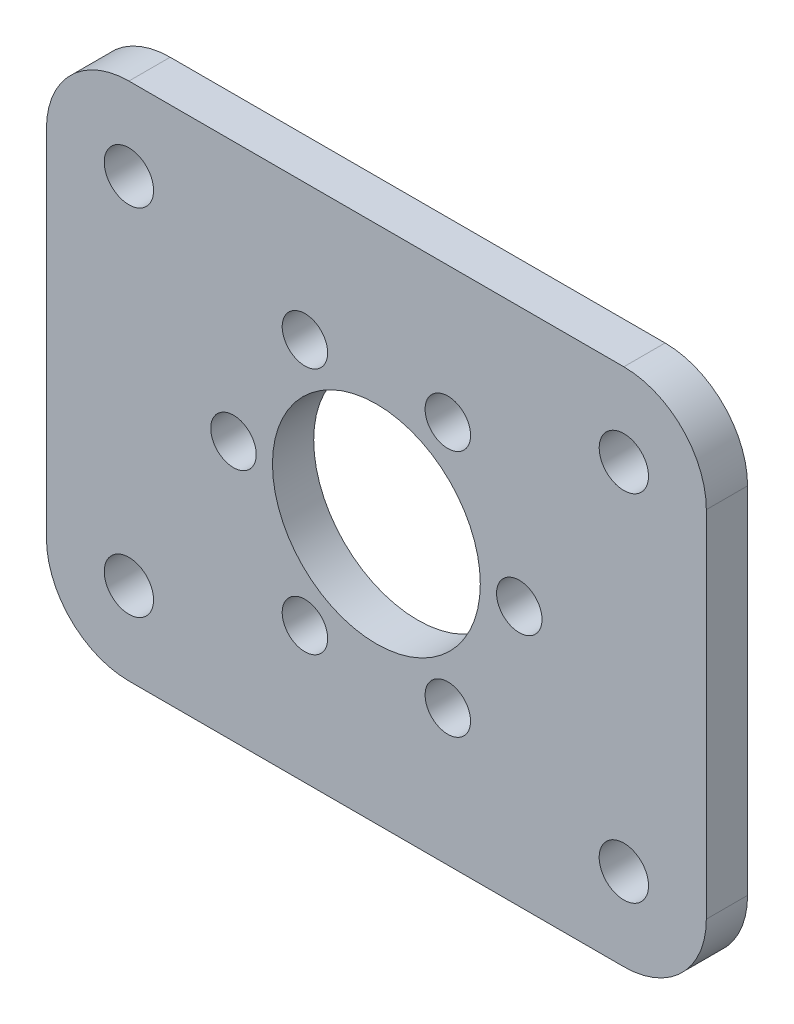
SolidWorks part; units mm, degrees
material "Balsa"
ref_plane "Front" through (0, 0, 0) normal (0, 0, 1) x (1, 0, 0)
ref_plane "Top" through (0, 0, 0) normal (0, 1, 0) x (1, 0, 0)
ref_plane "Right" through (0, 0, 0) normal (1, 0, 0) x (0, 0, -1)
sketch "Sketch1" plane through (0, 0, 0) normal (0, 0, 1) x (1, 0, 0)
  line L0 (25.4, 20) -> (-25.4, 20)
  line L1 (-25.4, 20) -> (-25.4, -20)
  line L2 (-25.4, -20) -> (25.4, -20)
  line L3 (0, 0) -> (0, 20) construction
  line L4 (25.4, 20) -> (25.4, -20)
  line L5 (0, 0) -> (-25.4, 0) construction
  circle A1 centre (0, 0) radius 8
  point P9 (0, -20)
  dimension "D1" = 16
  dimension "D2" = 40
  dimension "D3" = 25.4
extrude "Boss-Extrude1" add sketch "Sketch1" along normal blind 3.175
fillet "Fillet1" radius 6.35 4 edges at (-25.4, -20, 1.5875) (25.4, -20, 1.5875) (25.4, 20, 1.5875) (-25.4, 20, 1.5875)
sketch "Sketch8" plane through (0, 0, 3.175) normal (0, 0, 1) x (1, 0, 0)
  line L0 (-25.4, 0) -> (25.4, 0) construction
  line L1 (0, 0) -> (0, -22.225) construction
  line L3 (-25.4, 13.65) -> (-25.4, -13.65) construction
  line L6 (25.4, -13.65) -> (25.4, 13.65) construction
  line L7 (0, 0) -> (0, 20) construction
  line L8 (19.05, 20) -> (-19.05, 20) construction
  circle A0 centre (22.225, 0) radius 1.5
  circle A2 centre (-22.225, 0) radius 1.5
  circle A4 centre (0, 22.225) radius 1.5 [skipped]
  circle A5 centre (0, -22.225) radius 1.5 [skipped]
  dimension "D2" = 3
  dimension "D1" = 22.225
  dimension "D3" = 4
extrude "Cut-Extrude1" [suppressed] cut sketch "Sketch8" against normal through all
sketch "Sketch9" plane through (0, 0, 3.175) normal (0, 0, 1) x (1, 0, 0)
  line L0 (0, 0) -> (0, 20) construction
  line L1 (19.05, 20) -> (-19.05, 20) construction
  line L2 (0, 0) -> (-25.4, 0) construction
  line L3 (-25.4, 13.65) -> (-25.4, -13.65) construction
  line L4 (0, 0) -> (11, 0) construction
  line L5 (5.5, 9.5263) -> (0, 0) construction
  line L6 (0, 0) -> (-5.5, 9.5263) construction
  circle A0 centre (-19.05, 13.65) radius 1.632 construction
  circle A1 centre (-19.05, -13.65) radius 1.632 construction
  circle A2 centre (19.05, -13.65) radius 1.632 construction
  circle A3 centre (19.05, 13.65) radius 1.632 construction
  circle A4 centre (11, 0) radius 1.75
  circle A5 centre (5.5, -9.5263) radius 1.75
  circle A6 centre (-5.5, -9.5263) radius 1.75
  circle A7 centre (-11, 0) radius 1.75
  circle A8 centre (-5.5, 9.5263) radius 1.75
  circle A9 centre (5.5, 9.5263) radius 1.75
  dimension "D3" = 3.2639
  dimension "D4" = 11
  dimension "D6" = 3.5
  dimension "D1" = 6.35
  dimension "D2" = 6.35
  dimension "D5" = 6
extrude "M3-through" cut sketch "Sketch9" against normal through all
other "Move Face2" [suppressed] parameters "D1"=0.1
sketch "Sketch10" plane through (0, 0, 3.175) normal (0, 0, 1) x (1, 0, 0)
  line L0 (-19.05, -20) -> (19.05, -20) construction
  line L1 (25.4, -13.65) -> (25.4, 13.65) construction
  line L2 (0, 0) -> (27.673, 0) construction
  line L3 (0, 0) -> (0, 21.5313) construction
  circle A0 centre (19.05, -13.65) radius 1.8986
  circle A1 centre (19.05, 13.65) radius 1.8986
  circle A2 centre (-19.05, -13.65) radius 1.8986
  circle A3 centre (-19.05, 13.65) radius 1.8986
  dimension "D3" = 3.7973
  dimension "D1" = 6.35
  dimension "D2" = 6.35
extrude "Cut-Extrude2" cut sketch "Sketch10" against normal through all
